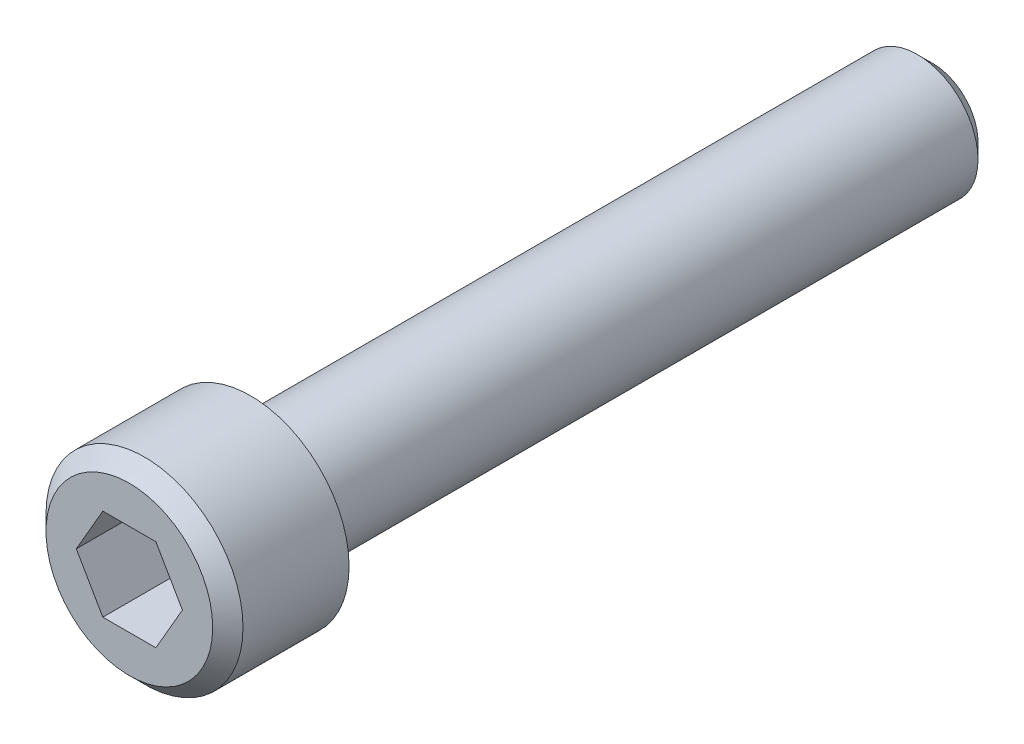
SolidWorks part; units mm, degrees
ref_plane "Alzado" through (0, 0, 0) normal (0, 0, 1) x (1, 0, 0)
ref_plane "Planta" through (0, 0, 0) normal (0, 1, 0) x (1, 0, 0)
ref_plane "Vista lateral" through (0, 0, 0) normal (1, 0, 0) x (0, 0, -1)
sketch "Croquis1" plane through (0, 0, 0) normal (0, 0, 1) x (1, 0, 0)
  circle A0 centre (0, 0) radius 6.5
  dimension "D1" = 13
extrude "Saliente-Extruir1" add sketch "Croquis1" along normal blind 8
sketch "Croquis2" plane through (0, 0, 0) normal (0, 0, -1) x (-1, 0, 0)
  circle A0 centre (0, 0) radius 4
  dimension "D1" = 8
extrude "Saliente-Extruir2" add sketch "Croquis2" along normal blind 45
chamfer "Chaflán1" distance 1 angle 45 2 edges at (6.5, 0, 8) (-4, 0, -45)
sketch "Croquis3" plane through (0, 0, 8) normal (0, 0, 1) x (1, 0, 0)
  line L1 (3.5, 0) -> (1.75, 3.0311)
  line L2 (1.75, 3.0311) -> (-1.75, 3.0311)
  line L3 (-1.75, 3.0311) -> (-3.5, 0)
  line L4 (-3.5, 0) -> (-1.75, -3.0311)
  line L5 (-1.75, -3.0311) -> (1.75, -3.0311)
  line L6 (1.75, -3.0311) -> (3.5, 0)
  circle A0 centre (0, 0) radius 3.0311 construction
  dimension "D1" = 7
extrude "Cortar-Extruir1" cut sketch "Croquis3" against normal blind 6
